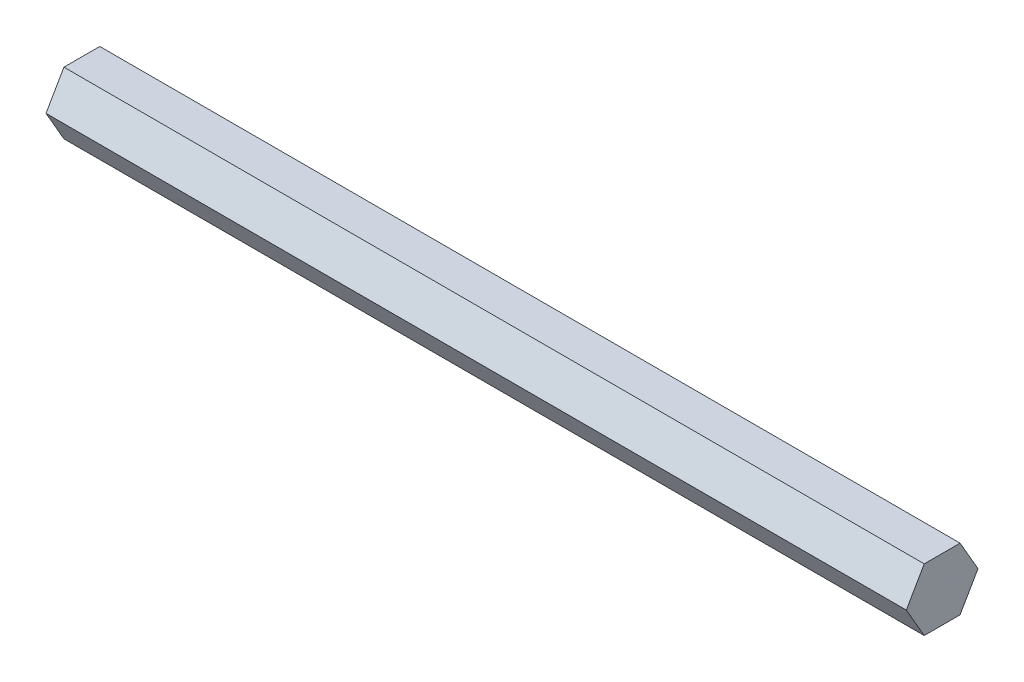
SolidWorks part; units mm, degrees
ref_plane "Front Plane" through (0, 0, 0) normal (0, 0, 1) x (1, 0, 0)
ref_plane "Top Plane" through (0, 0, 0) normal (0, 1, 0) x (1, 0, 0)
ref_plane "Right Plane" through (0, 0, 0) normal (1, 0, 0) x (0, 0, -1)
sketch "Sketch1" plane through (0, 0, 0) normal (1, 0, 0) x (0, 0, -1)
  line L1 (4.7625, 0) -> (2.3812, 4.1244)
  line L2 (2.3812, 4.1244) -> (-2.3813, 4.1244)
  line L3 (-2.3813, 4.1244) -> (-4.7625, 0)
  line L4 (-4.7625, 0) -> (-2.3812, -4.1244)
  line L5 (-2.3812, -4.1244) -> (2.3813, -4.1244)
  line L6 (2.3813, -4.1244) -> (4.7625, 0)
  circle A0 centre (0, 0) radius 4.1244 construction
  dimension "D1" = 9.525
extrude "Boss-Extrude1" add sketch "Sketch1" along normal blind 114.3
